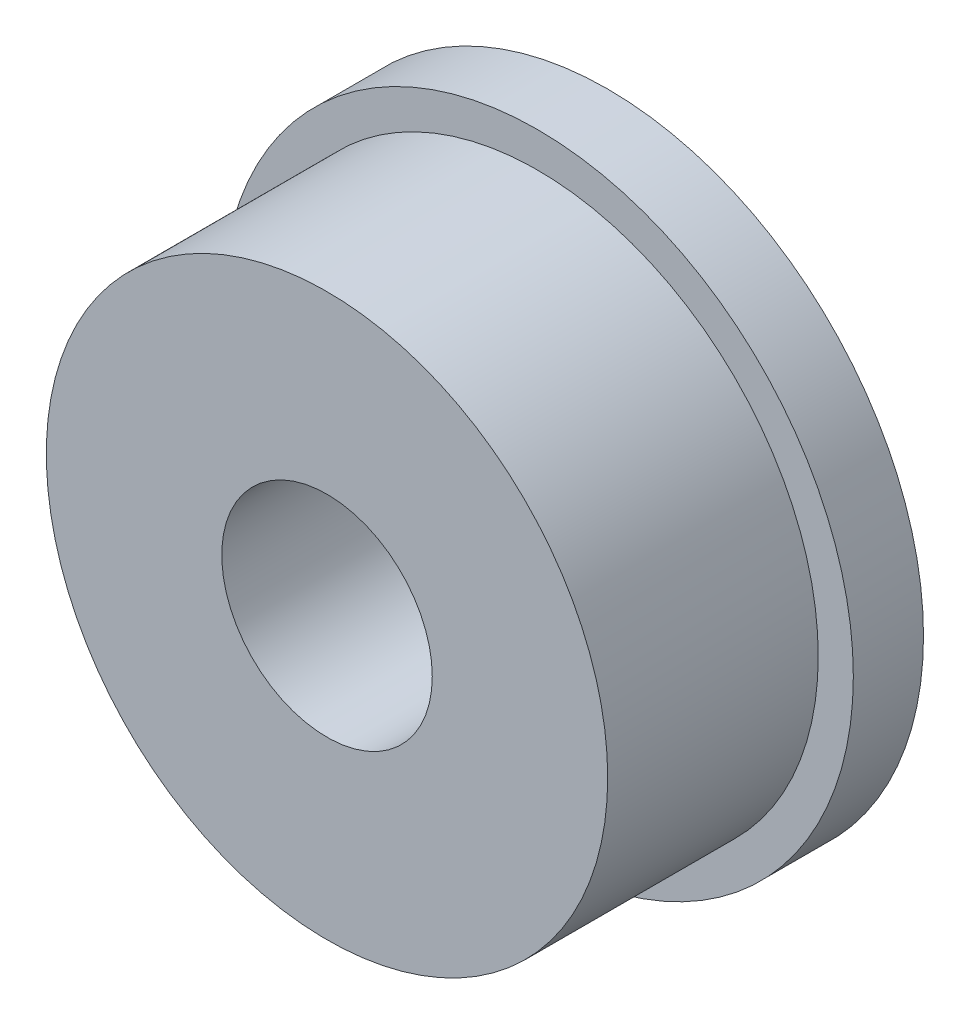
SolidWorks part; units mm, degrees
ref_plane "前视基准面" through (0, 0, 0) normal (0, 0, 1) x (1, 0, 0)
ref_plane "上视基准面" through (0, 0, 0) normal (0, 1, 0) x (1, 0, 0)
ref_plane "右视基准面" through (0, 0, 0) normal (1, 0, 0) x (0, 0, -1)
sketch "草图1" plane through (0, 0, 0) normal (0, 0, 1) x (1, 0, 0)
  circle A0 centre (0, 0) radius 4.5
extrude "凸台-拉伸1" add sketch "草图1" along normal blind 1
sketch "草图2" plane through (0, 0, 1) normal (0, 0, 1) x (1, 0, 0)
  circle A0 centre (0, 0) radius 4
extrude "凸台-拉伸2" add sketch "草图2" along normal blind 3
sketch "草图3" plane through (0, 0, 4) normal (0, 0, 1) x (1, 0, 0)
  circle A0 centre (0, 0) radius 1.5
extrude "切除-拉伸1" cut sketch "草图3" against normal through all
